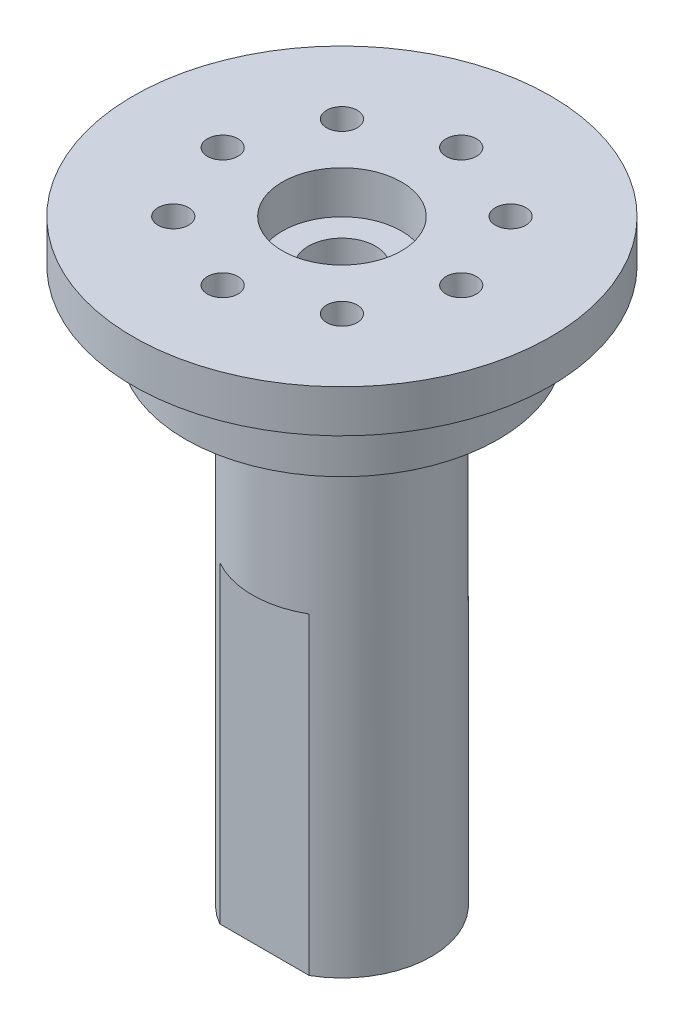
SolidWorks part; units mm, degrees
ref_plane "Front Plane" through (0, 0, 0) normal (0, 0, 1) x (1, 0, 0)
ref_plane "Top Plane" through (0, 0, 0) normal (0, 1, 0) x (1, 0, 0)
ref_plane "Right Plane" through (0, 0, 0) normal (1, 0, 0) x (0, 0, -1)
sketch "Sketch3" plane through (0, 0, 0) normal (0, 0, 1) x (1, 0, 0)
  line L0 (0, 0) -> (0, 5893.2608) construction
  line L1 (-2.25, 34.3) -> (0, 34.3)
  line L2 (0, 34.3) -> (0, 0)
  line L7 (-10.5, 37.15) -> (-14, 37.15)
  line L8 (-14, 37.15) -> (-14, 40)
  line L9 (-14, 40) -> (-4, 40)
  line L10 (-4, 40) -> (-4, 37.15)
  line L11 (-4, 37.15) -> (-2.25, 37.15)
  line L12 (-2.25, 37.15) -> (-2.25, 34.3)
  line L14 (-6, 0) -> (0, 0)
  line L15 (-10.5, 37.15) -> (-10.5, 32.3)
  line L16 (-10.5, 32.3) -> (-6, 32.3)
  line L17 (-6, 32.3) -> (-6, 0)
  dimension "D1" = 4
  dimension "D2" = 14
  dimension "D3" = 2.25
  dimension "D4" = 2.85
  dimension "D5" = 40
  dimension "D6" = 2.85
  dimension "D7" = 6
  dimension "D8" = 3.5
  dimension "D9" = 2
revolve "Revolve1" add sketch "Sketch3" angle 360 about L0
sketch "Sketch6" plane through (0, 32.3, 0) normal (0, -1, 0) x (1, 0, 0)
  circle A0 centre (0, 0) radius 8 construction
  circle A1 centre (0, 8) radius 1
  circle A2 centre (5.6569, 5.6569) radius 1
  circle A3 centre (8, 0) radius 1
  circle A4 centre (5.6569, -5.6569) radius 1
  circle A5 centre (0, -8) radius 1
  circle A6 centre (-5.6569, -5.6569) radius 1
  circle A7 centre (-8, 0) radius 1
  circle A8 centre (-5.6569, 5.6569) radius 1
  point P3 (0, 8)
  point P8 (5.6569, 5.6569)
  point P10 (8, 0)
  point P12 (5.6569, -5.6569)
  point P14 (0, -8)
  point P16 (-5.6569, -5.6569)
  point P18 (-8, 0)
  point P20 (-5.6569, 5.6569)
  point P22 (0, 0)
  point P39 (-5.6569, 5.6569)
  dimension "D1" = 16
  dimension "D2" = 2
  dimension "D3" = 8
hole_wizard "Tap Drill for M2.5x0.45 Tap2" positions "Sketch6" profile "Sketch12" hole size "M2.5x0.45" standard "ANSI Metric"
sketch "Sketch12" plane through (-5.6569, 32.3, 5.6569) normal (1, 0, 0) x (0, 0, -1)
  line L0 (0, 0) -> (0, 7.7)
  line L1 (0, 7.7) -> (1.025, 7.7)
  line L2 (1.025, 7.7) -> (1.025, 0)
  line L5 (1.025, 0) -> (0, 0)
  line L11 (0, -6.35) -> (0, 107.95) construction
  dimension "Thru Hole Dia." = 2.05
  dimension "Thru Hole Depth" = 7.7
sketch "Sketch13" plane through (0, 0, 0) normal (0, -1, 0) x (1, 0, 0)
  line L0 (-3, 5.1962) -> (3, 5.1962)
  circle A0 centre (0, 0) radius 6 construction
  circle A1 centre (0, 0) radius 6 construction
  circle A2 centre (0, 0) radius 6
  circle M2 centre (0, 0) radius 6
  dimension "D1" = 6
extrude "Cut-Extrude1" cut sketch "Sketch13" against normal blind 21 contours L0 M2
